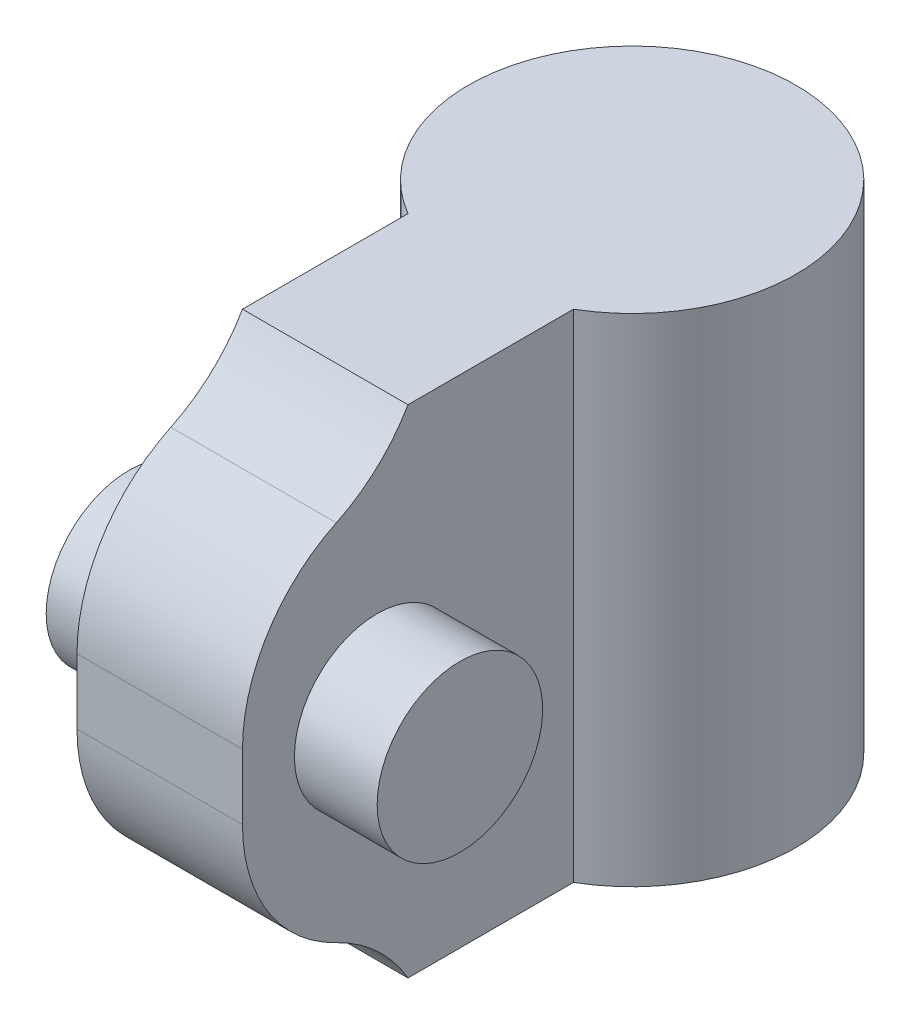
SolidWorks part; units mm, degrees
ref_plane "Front Plane" through (0, 0, 0) normal (0, 0, 1) x (1, 0, 0)
ref_plane "Top Plane" through (0, 0, 0) normal (0, 1, 0) x (1, 0, 0)
ref_plane "Right Plane" through (0, 0, 0) normal (1, 0, 0) x (0, 0, -1)
ref_plane "Plane1" through (0, -15, 0) normal (0, -1, 0) x (1, 0, 0)
sketch "Sketch1" plane through (0, -15, 0) normal (0, -1, 0) x (1, 0, 0)
  line L0 (-2.5, 14.2723) -> (-2.5, 4.2723)
  line L1 (2.5, 4.2723) -> (2.5, 14.2723)
  line L2 (2.5, 14.2723) -> (-2.5, 14.2723)
  arc A0 (-2.5, 4.2723) -> (2.5, 4.2723) centre (0, 0) ccw
extrude "Boss-Extrude1" add sketch "Sketch1" against normal blind 15
sketch "Sketch2" plane through (2.5, 0, 0) normal (1, 0, 0) x (0, 0, -1)
  line L0 (-14.2723, -15) -> (-9.2723, -15)
  line L1 (-14.2723, -8.4861) -> (-14.2723, -15)
  arc A0 (-9.2723, -15) -> (-11.4374, -12.9931) centre (-13.6024, -17.5) ccw
  arc A1 (-11.4374, -12.9931) -> (-14.2723, -8.4861) centre (-9.2723, -8.4861) cw
extrude "Cut-Extrude1" cut sketch "Sketch2" against normal through all
sketch "Sketch3" plane through (2.5, 0, 0) normal (1, 0, 0) x (0, 0, -1)
  line L0 (-9.2723, 0) -> (-14.2723, 0)
  line L1 (-14.2723, 0) -> (-14.2723, -6.5139)
  arc A0 (-14.2723, -6.5139) -> (-11.4374, -2.0069) centre (-9.2723, -6.5139) cw
  arc A1 (-11.4374, -2.0069) -> (-9.2723, 0) centre (-13.6024, 2.5) ccw
extrude "Cut-Extrude2" cut sketch "Sketch3" against normal through all
ref_plane "Plane2" through (0, 0, 10.2033) normal (0, 0, -1) x (-1, 0, 0)
sketch "Sketch4" plane through (0, 0, 10.2033) normal (0, 0, -1) x (-1, 0, 0)
  line L0 (2.5, -5) -> (2.5, -7.5)
  line L1 (2.5, -7.5) -> (5, -7.5)
  line L2 (5, -7.5) -> (5, -5)
  line L3 (5, -5) -> (2.5, -5)
  line L4 (2.5, -7.5) -> (5, -7.5) construction
revolve "Revolve1" add sketch "Sketch4" angle 360 about L4
sketch "Sketch5" plane through (0, 0, 10.2033) normal (0, 0, -1) x (-1, 0, 0)
  line L0 (-5, -5) -> (-5, -7.5)
  line L1 (-5, -7.5) -> (-2.5, -7.5)
  line L2 (-2.5, -7.5) -> (-2.5, -5)
  line L3 (-2.5, -5) -> (-5, -5)
  line L4 (-5, -7.5) -> (-2.5, -7.5) construction
revolve "Revolve2" add sketch "Sketch5" angle 360 about L4
